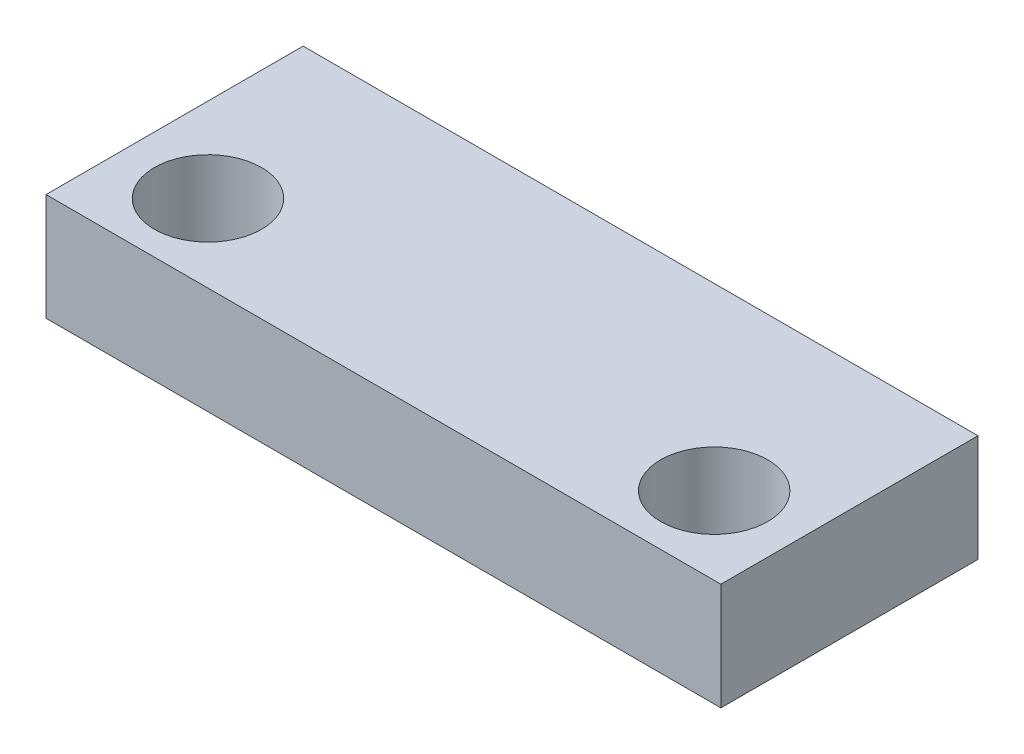
SolidWorks part; units mm, degrees
ref_plane "Front Plane" through (0, 0, 0) normal (0, 0, 1) x (1, 0, 0)
ref_plane "Top Plane" through (0, 0, 0) normal (0, 1, 0) x (1, 0, 0)
ref_plane "Right Plane" through (0, 0, 0) normal (1, 0, 0) x (0, 0, -1)
sketch "Sketch2" plane through (0, 0, 0) normal (0, 1, 0) x (1, 0, 0)
  line L0 (0, 0) -> (0, 7.62)
  line L1 (0, 7.62) -> (20, 7.62)
  line L2 (20, 7.62) -> (20, 0)
  line L3 (20, 0) -> (0, 0)
  line L4 (10, 15.24) -> (10, 0) construction
  circle A0 centre (17.5006, 2.3012) radius 1.5875
  circle A1 centre (2.4994, 2.3012) radius 1.5875
  point P10 (10, 7.62)
  dimension "D3" = 3.175
  dimension "D1" = 20
  dimension "D2" = 7.62
  dimension "D4" = 2.4994
  dimension "D5" = 2.3012
extrude "Boss-Extrude1" add sketch "Sketch2" against normal blind 3.175
